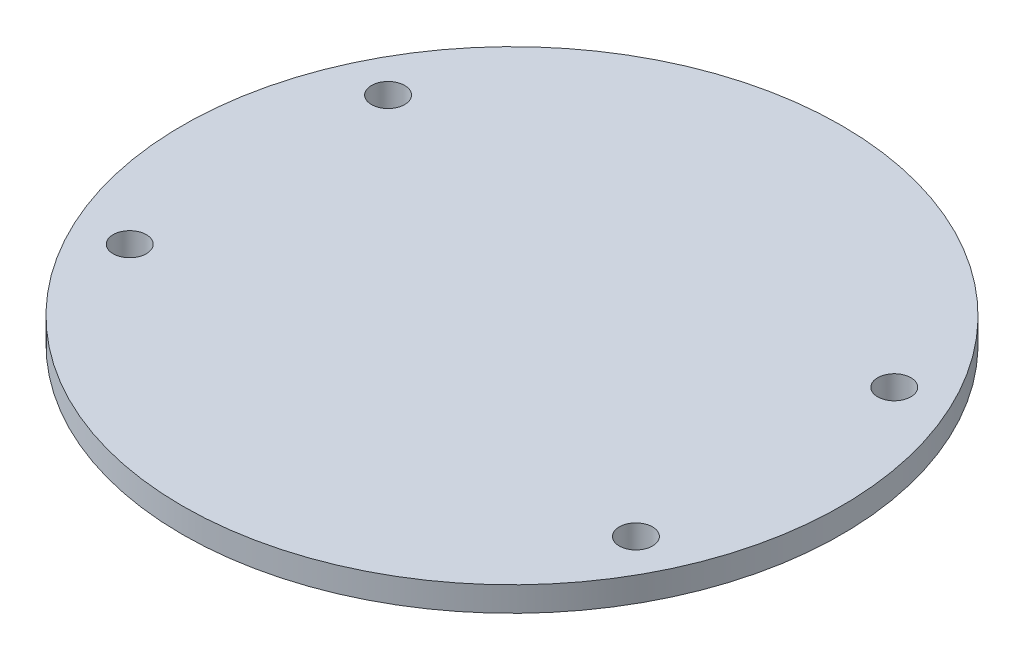
SolidWorks part; units mm, degrees
ref_plane "Front Plane" through (0, 0, 0) normal (0, 0, 1) x (1, 0, 0)
ref_plane "Top Plane" through (0, 0, 0) normal (0, 1, 0) x (1, 0, 0)
ref_plane "Right Plane" through (0, 0, 0) normal (1, 0, 0) x (0, 0, -1)
sketch "Sketch1" plane through (0, 0, 0) normal (0, 1, 0) x (1, 0, 0)
  circle A0 centre (0, 0) radius 31.75
  circle A1 centre (-24.384, -12.446) radius 1.6
  circle A2 centre (-24.384, 12.446) radius 1.6
  circle A3 centre (24.384, -12.446) radius 1.6
  circle A4 centre (24.384, 12.446) radius 1.6
  dimension "D1" = 63.5
  dimension "D2" = 3.2
  dimension "D3" = 24.384
  dimension "D4" = 12.446
  dimension "D5" = 24.384
  dimension "D6" = 12.446
extrude "Boss-Extrude1" add sketch "Sketch1" along normal blind 2.3813 contours A0 A4 A3 A2 A1
